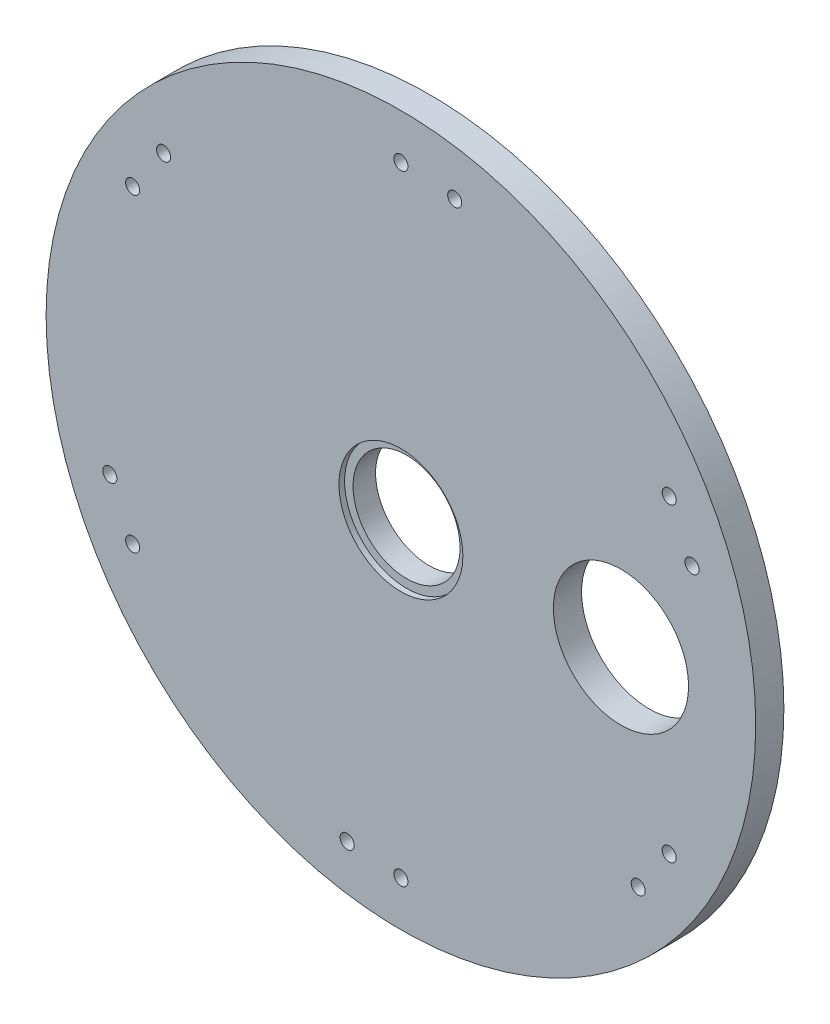
SolidWorks part; units mm, degrees
ref_plane "前视基准面" through (0, 0, 0) normal (0, 0, 1) x (1, 0, 0)
ref_plane "上视基准面" through (0, 0, 0) normal (0, 1, 0) x (1, 0, 0)
ref_plane "右视基准面" through (0, 0, 0) normal (1, 0, 0) x (0, 0, -1)
sketch "草图1" plane through (0, 0, 0) normal (0, 0, 1) x (1, 0, 0)
  line L1 (0, 55) -> (-47.6314, 27.5) construction
  line L2 (-47.6314, 27.5) -> (-47.6314, -27.5) construction
  line L3 (-47.6314, -27.5) -> (0, -55) construction
  line L4 (0, -55) -> (47.6314, -27.5) construction
  line L5 (47.6314, -27.5) -> (47.6314, 27.5) construction
  line L6 (47.6314, 27.5) -> (0, 55) construction
  line L7 (-42.1324, 35.3533) -> (-51.6831, -18.8111) construction
  line L8 (-51.6831, -18.8111) -> (-9.5506, -54.1644) construction
  line L9 (-9.5506, -54.1644) -> (42.1324, -35.3533) construction
  line L10 (42.1324, -35.3533) -> (51.6831, 18.8111) construction
  line L11 (51.6831, 18.8111) -> (9.5506, 54.1644) construction
  line L12 (9.5506, 54.1644) -> (-42.1324, 35.3533) construction
  circle A0 centre (0, 0) radius 63
  circle A1 centre (0, 0) radius 47.6314 construction
  circle A2 centre (0, 55) radius 1.25
  circle A3 centre (47.6314, 27.5) radius 1.25
  circle A4 centre (47.6314, -27.5) radius 1.25
  circle A5 centre (0, -55) radius 1.25
  circle A6 centre (-47.6314, -27.5) radius 1.25
  circle A7 centre (-47.6314, 27.5) radius 1.25
  circle A8 centre (0, 0) radius 47.6314 construction
  circle A9 centre (-42.1324, 35.3533) radius 1.25
  circle A10 centre (9.5506, 54.1644) radius 1.25
  circle A11 centre (51.6831, 18.8111) radius 1.25
  circle A12 centre (42.1324, -35.3533) radius 1.25
  circle A13 centre (-9.5506, -54.1644) radius 1.25
  circle A14 centre (-51.6831, -18.8111) radius 1.25
  point P24 (0, 0)
  dimension "D1" = 126
  dimension "D4" = 2.5
  dimension "D2" = 110
  dimension "D5" = 170
  dimension "D3" = 6
extrude "凸台-拉伸1" add sketch "草图1" along normal blind 5
sketch "草图2" plane through (0, 0, 5) normal (0, 0, 1) x (1, 0, 0)
  circle A0 centre (39.073, 0) radius 12
  dimension "D1" = 24
extrude "切除-拉伸4" cut sketch "草图2" against normal blind 5
sketch "草图3" plane through (0, 0, 5) normal (0, 0, 1) x (1, 0, 0)
  circle A0 centre (0, 0) radius 9.5
  dimension "D1" = 19
extrude "切除-拉伸5" cut sketch "草图3" against normal blind 10
sketch "草图4" plane through (0, 0, 5) normal (0, 0, 1) x (1, 0, 0)
  circle A0 centre (0, 0) radius 11
  circle A1 centre (0, 0) radius 9.5 construction
  dimension "D1" = 1.5
extrude "切除-拉伸6" cut sketch "草图4" against normal blind 1
